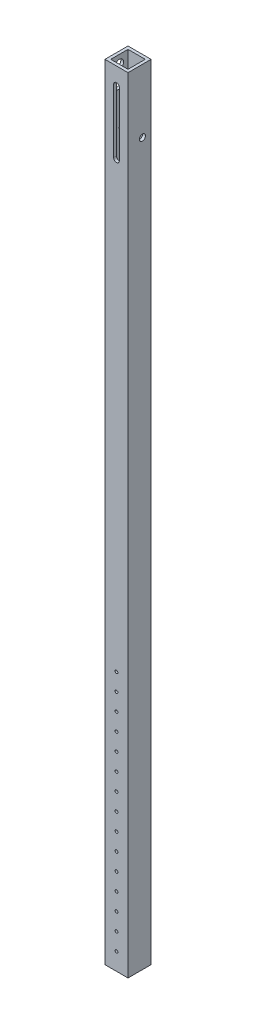
SolidWorks part; units mm, degrees
material "6061-T6 (SS)"
ref_plane "Front Plane" through (0, 0, 0) normal (0, 0, 1) x (1, 0, 0)
ref_plane "Top Plane" through (0, 0, 0) normal (0, 1, 0) x (1, 0, 0)
ref_plane "Right Plane" through (0, 0, 0) normal (1, 0, 0) x (0, 0, -1)
sketch "Sketch1" plane through (0, 0, 0) normal (0, 1, 0) x (1, 0, 0)
  line L0 (9.525, 9.525) -> (-9.525, 9.525)
  line L1 (12.7, -12.7) -> (-12.7, -12.7)
  line L2 (12.7, -12.7) -> (12.7, 12.7)
  line L3 (12.7, 12.7) -> (-12.7, 12.7)
  line L4 (-12.7, -12.7) -> (-12.7, 12.7)
  line L5 (12.7, -12.7) -> (-12.7, 12.7) construction
  line L6 (12.7, 12.7) -> (-12.7, -12.7) construction
  line L7 (-9.525, -9.525) -> (-9.525, 9.525)
  line L8 (9.525, -9.525) -> (-9.525, -9.525)
  line L9 (9.525, -9.525) -> (9.525, 9.525)
  point P0 (0, 0)
  dimension "D1" = 25.4
  dimension "D2" = 3.175
extrude "Boss-Extrude1" add sketch "Sketch1" along normal blind 863.6
sketch "Sketch2" plane through (0, 0, -12.7) normal (0, 0, -1) x (-1, 0, 0)
  line L0 (0, 711.2) -> (0, 825.5) construction
  line L1 (-3.175, 711.2) -> (-3.175, 825.5)
  line L2 (3.175, 711.2) -> (3.175, 825.5)
  line L3 (-12.7, 863.6) -> (12.7, 863.6) construction
  arc A0 (-3.175, 711.2) -> (3.175, 711.2) centre (0, 711.2) ccw
  arc A1 (3.175, 825.5) -> (-3.175, 825.5) centre (0, 825.5) ccw
  point P3 (0, 768.35)
  dimension "D2" = 38.1
  dimension "D1" = 6.35
  dimension "D3" = 114.3
extrude "Cut-Extrude1" cut sketch "Sketch2" against normal up to next
sketch "Sketch3" plane through (0, 0, 12.7) normal (0, 0, 1) x (1, 0, 0)
  line L0 (0, 844.55) -> (0, 774.7) construction
  line L1 (3.175, 844.55) -> (3.175, 774.7)
  line L2 (-3.175, 844.55) -> (-3.175, 774.7)
  line L3 (-12.7, 863.6) -> (12.7, 863.6) construction
  arc A0 (3.175, 844.55) -> (-3.175, 844.55) centre (0, 844.55) ccw
  arc A1 (-3.175, 774.7) -> (3.175, 774.7) centre (0, 774.7) ccw
  point P3 (0, 809.625)
  dimension "D2" = 19.05
  dimension "D1" = 6.35
  dimension "D3" = 69.85
extrude "Cut-Extrude2" cut sketch "Sketch3" against normal up to next
sketch "Sketch4" plane through (-12.7, 0, 0) normal (-1, 0, 0) x (0, 0, 1)
  line L0 (-12.7, 863.6) -> (12.7, 863.6) construction
  line L2 (-12.7, 863.6) -> (-12.7, 0) construction
  circle A0 centre (-3.175, 793.75) radius 3.3782
  dimension "D1" = 6.7564
  dimension "D2" = 69.85
  dimension "D3" = 9.525
extrude "Cut-Extrude3" cut sketch "Sketch4" against normal through all
sketch "Sketch5" plane through (-12.7, 0, 0) normal (-1, 0, 0) x (0, 0, 1)
  line L0 (-12.7, 863.6) -> (-12.7, 0) construction
  line L1 (-12.7, 863.6) -> (12.7, 863.6) construction
  line L2 (-12.7, 863.6) -> (-12.7, 825.5) construction
  circle A0 centre (0, 854.075) radius 4.7625
  circle A1 centre (0, 835.025) radius 4.7625
  dimension "D1" = 9.525
  dimension "D2" = 12.7
  dimension "D3" = 9.525
  dimension "D4" = 38.1
  dimension "D5" = 9.525
extrude "Cut-Extrude4" cut sketch "Sketch5" against normal up to next
sketch "Sketch6" plane through (0, 0, 12.7) normal (0, 0, 1) x (1, 0, 0)
  line L0 (-12.7, 0) -> (-12.7, 304.8) construction
  line L1 (-12.7, 863.6) -> (-12.7, 0) construction
  line L2 (-12.7, 0) -> (12.7, 0) construction
  line L3 (12.7, 863.6) -> (12.7, 0) construction
  circle A28 centre (0, 19.05) radius 1.5875
  circle A29 centre (0, 38.1) radius 1.5875
  circle A30 centre (0, 57.15) radius 1.5875
  circle A31 centre (0, 76.2) radius 1.5875
  circle A32 centre (0, 95.25) radius 1.5875
  circle A33 centre (0, 114.3) radius 1.5875
  circle A34 centre (0, 133.35) radius 1.5875
  circle A35 centre (0, 152.4) radius 1.5875
  circle A36 centre (0, 171.45) radius 1.5875
  circle A37 centre (0, 190.5) radius 1.5875
  circle A38 centre (0, 209.55) radius 1.5875
  circle A39 centre (0, 228.6) radius 1.5875
  circle A40 centre (0, 247.65) radius 1.5875
  circle A41 centre (0, 266.7) radius 1.5875
  circle A42 centre (0, 285.75) radius 1.5875
  dimension "D3" = 19.05
  dimension "D5" = 15
  dimension "D6" = 19.05
  dimension "D2" = 3.175
  dimension "D4" = 12.7
  dimension "D1" = 304.8
extrude "Cut-Extrude5" cut sketch "Sketch6" against normal through all
